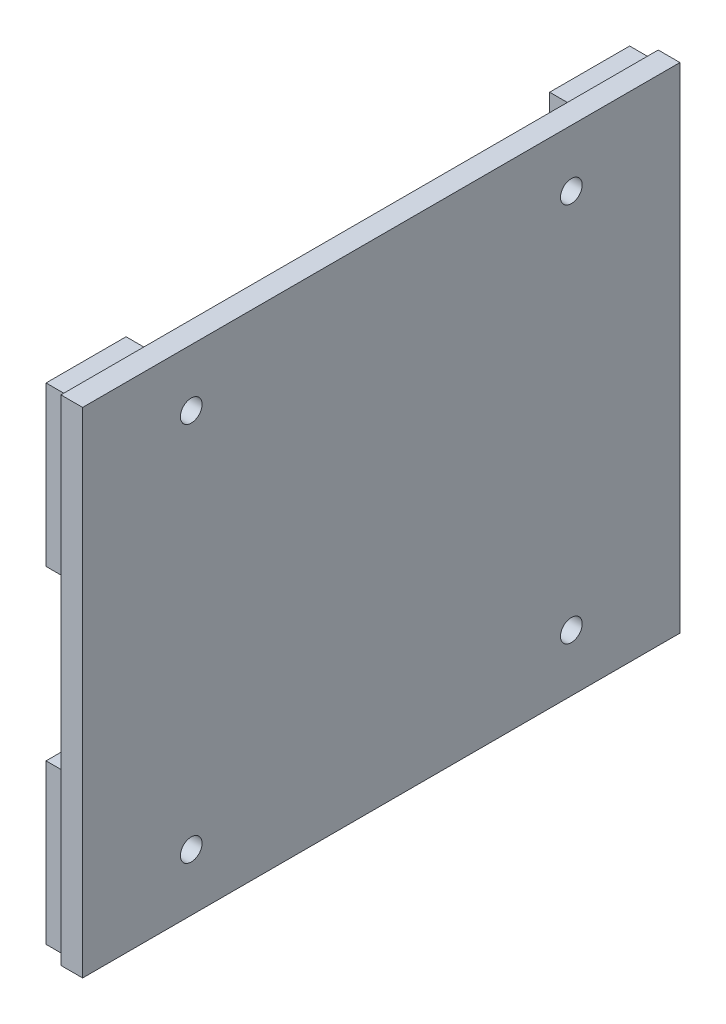
SolidWorks part; units mm, degrees
ref_plane "Front Plane" through (0, 0, 0) normal (0, 0, 1) x (1, 0, 0)
ref_plane "Top Plane" through (0, 0, 0) normal (0, 1, 0) x (1, 0, 0)
ref_plane "Right Plane" through (0, 0, 0) normal (1, 0, 0) x (0, 0, -1)
sketch "Sketch1" plane through (0, 0, 0) normal (1, 0, 0) x (0, 0, -1)
  line L0 (-55.5625, 55.5625) -> (55.5625, -55.5625) construction
  line L1 (-87.3125, -72.2313) -> (87.3125, -72.2313)
  line L2 (-87.3125, -72.2313) -> (-87.3125, 72.2313)
  line L3 (-87.3125, 72.2313) -> (87.3125, 72.2313)
  line L4 (87.3125, -72.2313) -> (87.3125, 72.2313)
  line L5 (55.5625, -55.5625) -> (55.5625, 55.5625) construction
  line L6 (55.5625, 55.5625) -> (-55.5625, -55.5625) construction
  line L7 (-55.5625, 55.5625) -> (55.5625, 55.5625) construction
  line L8 (-55.5625, 55.5625) -> (-55.5625, -55.5625) construction
  line L9 (-55.5625, -55.5625) -> (55.5625, -55.5625) construction
  line L10 (55.5625, 55.5625) -> (55.5625, -55.5625) construction
  line L11 (-87.3125, 72.2313) -> (87.3125, -72.2313) construction
  line L12 (87.3125, 72.2313) -> (-87.3125, -72.2313) construction
  circle A0 centre (-55.5625, 55.5625) radius 3.175
  circle A1 centre (55.5625, 55.5625) radius 3.175
  circle A2 centre (55.5625, -55.5625) radius 3.175
  circle A3 centre (-55.5625, -55.5625) radius 3.175
  point P0 (0, 0)
  point P6 (0, 0)
  dimension "D5" = 6.35
  dimension "D1" = 174.625
  dimension "D2" = 144.4625
  dimension "D3" = 111.125
  dimension "D4" = 111.125
extrude "Boss-Extrude1" add sketch "Sketch1" along normal blind 6.35
sketch "Sketch2" plane through (0, 0, 0) normal (-1, 0, 0) x (0, 0, 1)
  line L0 (61.9125, 71.0694) -> (85.3069, 71.0694)
  line L3 (85.3069, 24.6062) -> (61.9125, 24.6062)
  line L4 (61.9125, 71.0694) -> (61.9125, 24.6062)
  line L5 (0, -72.2313) -> (0, 72.2313) construction
  line L6 (87.3125, -72.2313) -> (-87.3125, -72.2313) construction
  line L7 (-87.3125, 0) -> (87.3125, 0) construction
  line L8 (-87.3125, -72.2313) -> (-87.3125, 72.2313) construction
  line L9 (87.3125, 72.2313) -> (87.3125, -72.2313) construction
  line L22 (85.3069, 24.6062) -> (85.3069, 71.0694)
  line L23 (-85.3069, 24.6062) -> (-85.3069, 71.0694)
  line L24 (-61.9125, 71.0694) -> (-85.3069, 71.0694)
  line L25 (-61.9125, 71.0694) -> (-61.9125, 24.6062)
  line L26 (-85.3069, 24.6062) -> (-61.9125, 24.6062)
  line L27 (-85.3069, -24.6062) -> (-61.9125, -24.6062)
  line L28 (-61.9125, -71.0694) -> (-61.9125, -24.6062)
  line L29 (-61.9125, -71.0694) -> (-85.3069, -71.0694)
  line L30 (-85.3069, -24.6062) -> (-85.3069, -71.0694)
  line L31 (85.3069, -24.6062) -> (85.3069, -71.0694)
  line L32 (61.9125, -71.0694) -> (85.3069, -71.0694)
  line L33 (61.9125, -71.0694) -> (61.9125, -24.6062)
  line L34 (85.3069, -24.6062) -> (61.9125, -24.6062)
extrude "Boss-Extrude2" add sketch "Sketch2" along normal blind 6.35
